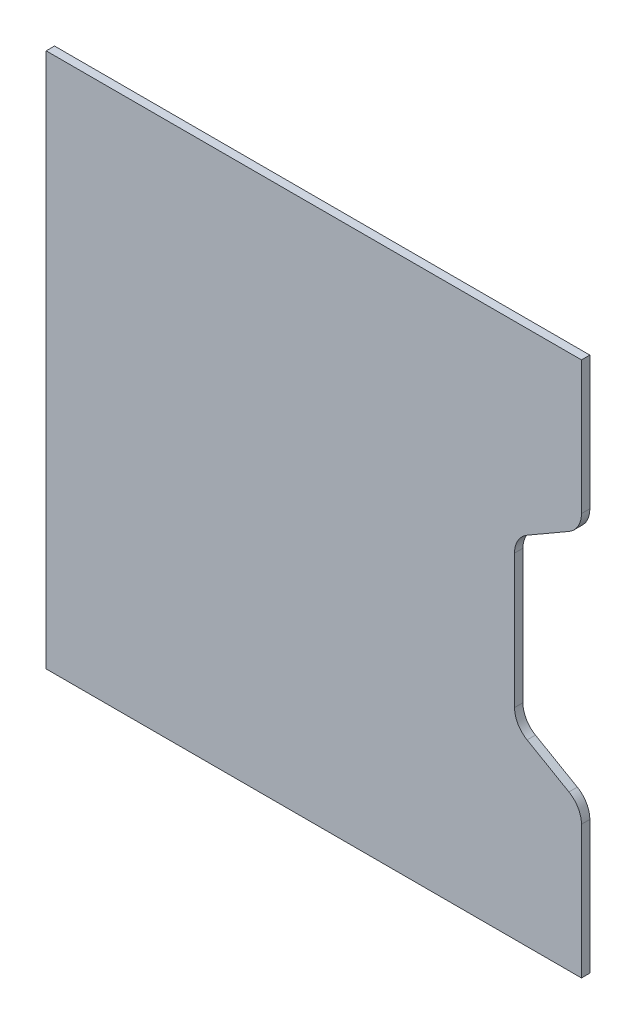
SolidWorks part; units mm, degrees
ref_plane "Front Plane" through (0, 0, 0) normal (0, 0, 1) x (1, 0, 0)
ref_plane "Top Plane" through (0, 0, 0) normal (0, 1, 0) x (1, 0, 0)
ref_plane "Right Plane" through (0, 0, 0) normal (1, 0, 0) x (0, 0, -1)
sketch "Sketch1" plane through (0, 0, 0) normal (0, 0, 1) x (1, 0, 0)
  line L1 (-101.6, -101.6) -> (101.6, -101.6)
  line L2 (-101.6, -101.6) -> (-101.6, 101.6)
  line L3 (-101.6, 101.6) -> (101.6, 101.6)
  line L4 (101.6, -101.6) -> (101.6, 101.6)
  line L5 (-101.6, -101.6) -> (101.6, 101.6) construction
  line L6 (-101.6, 101.6) -> (101.6, -101.6) construction
  point P0 (0, 0)
  dimension "D1" = 203.2
  dimension "D2" = 203.2
extrude "Boss-Extrude1" add sketch "Sketch1" against normal blind 3.175
sketch "Sketch4" plane through (0, 0, 0) normal (1, 0, 0) x (0, 0, -1)
  line L0 (0, 101.6) -> (0, -101.6) construction
  line L1 (0, 63.5) -> (-1.9844, 63.5)
  line L2 (0, 63.5) -> (0, 101.6)
  line L3 (0, 101.6) -> (-0.4801, 103.5254) construction
  line L4 (-1.9844, 63.5) -> (-1.9844, 101.6)
  line L5 (36.9683, 110.8172) -> (0, 101.6)
  line L6 (36.9683, 110.8172) -> (36.4882, 112.7427)
  line L7 (0, 101.6) -> (-1.9844, 101.6) construction
  line L8 (36.4882, 112.7427) -> (-0.4801, 103.5254)
  arc A0 (-0.4801, 103.5254) -> (-1.9844, 101.6) centre (-5.5035, 105.8998) ccw
  circle A1 centre (-5.5035, 105.8998) radius 3.7507
  dimension "D4" = 5.5562
  dimension "D1" = 1.9844
  dimension "D2" = 104
  dimension "D3" = 38.1
  dimension "D6" = 38.1
extrude "Boss-Extrude2" [suppressed] add sketch "Sketch4" along normal mid plane 203.2 separate body
sketch "Sketch5" [suppressed] plane through (0, 0, 1.9844) normal (0, 0, 1) x (1, 0, 0)
  line L0 (101.6, 63.5) -> (-101.6, 63.5) construction
  line L1 (-12.7, 63.5) -> (12.7, 63.5)
  line L2 (-12.7, 63.5) -> (-12.7, 116.2378)
  line L3 (-12.7, 116.2378) -> (12.7, 116.2378)
  line L4 (12.7, 63.5) -> (12.7, 116.2378)
  line L5 (-101.6, 101.6) -> (-101.6, 63.5) construction
  line L6 (101.6, 101.6) -> (101.6, 63.5) construction
  line L7 (-93.6625, 80.9625) -> (-101.6, 80.9625) construction
  line L8 (-93.6625, 80.9625) -> (-20.6375, 80.9625) construction
  line L9 (101.6, 101.6) -> (-101.6, 101.6) construction
  line L11 (0, 101.6) -> (0, 63.5) construction
  line L12 (-20.6375, 80.9625) -> (-12.7, 80.9625) construction
  line L13 (-57.15, 80.9625) -> (-57.15, 72.2313) construction
  line L14 (-57.15, 72.2313) -> (-57.15, 63.5) construction
  circle A0 centre (-93.6625, 80.9625) radius 4.3656
  circle A1 centre (-20.6375, 80.9625) radius 4.3656
  circle A2 centre (20.6375, 80.9625) radius 4.3656
  circle A3 centre (93.6625, 80.9625) radius 4.3656
  circle A4 centre (-57.15, 72.2313) radius 4.3656
  circle A5 centre (57.15, 72.2312) radius 4.3656
  dimension "D5" = 8.7312
  dimension "D3" = 8.7312
  dimension "D1" = 88.9
  dimension "D2" = 88.9
  dimension "D4" = 17.4625
  dimension "D6" = 7.9375
extrude "Cut-Extrude1" [suppressed] cut sketch "Sketch5" against normal through all both and the other way through all
sketch "Sketch6" [suppressed] plane through (0, 97.5792, 24.3292) normal (0, 0.9703, 0.2419) x (1, 0, 0)
  line L0 (101.6, 62.6793) -> (12.7, 62.6793) construction
  line L1 (12.7, 62.6793) -> (12.7, 24.5793) construction
  line L2 (-12.7, 24.5793) -> (-12.7, 62.6793) construction
  line B0 (93.6625, 45.2168) -> (101.6, 45.2168) construction
  line B1 (93.6625, 45.2168) -> (20.6375, 45.2168) construction
  line B2 (20.6375, 45.2168) -> (12.7, 45.2168) construction
  line B3 (57.15, 45.2168) -> (57.15, 53.948) construction
  line B4 (57.15, 53.948) -> (57.15, 62.6793) construction
  circle B5 centre (93.6625, 45.2168) radius 4.3656
  circle B6 centre (20.6375, 45.2168) radius 4.3656
  circle B7 centre (57.15, 53.948) radius 4.3656
  circle B8 centre (-20.6375, 43.6293) radius 4.3656
  circle B9 centre (-93.6625, 43.6293) radius 4.3656
  circle B10 centre (-57.15, 52.3605) radius 4.3656
sketch_block_instance "Block2-1"
sketch_block "Block2" parameters "D1"=8.7312
sketch_block_instance "Block2-2"
extrude "Cut-Extrude2" [suppressed] cut sketch "Sketch6" against normal through all
sketch "Sketch8" plane through (0, 0, 0) normal (0, 0, 1) x (1, 0, 0)
  line L0 (0, 0) -> (0, 57) construction
  line L1 (-49.3634, -28.5) -> (0, 0) construction
  line L2 (49.3634, -28.5) -> (0, 0) construction
  circle A0 centre (0, 0) radius 50.5
  circle A1 centre (0, 0) radius 57 construction
  circle A2 centre (0, 57) radius 4.25
  circle A3 centre (-49.3634, -28.5) radius 4.25
  circle A4 centre (49.3634, -28.5) radius 4.25
  dimension "D1" = 101
  dimension "D4" = 114
  dimension "D5" = 8.5
  dimension "D2" = 120
  dimension "D3" = 120
extrude "Cut-Extrude3" [suppressed] cut sketch "Sketch8" against normal through all
sketch "Sketch9" plane through (0, 0, 0) normal (0, 0, 1) x (1, 0, 0)
  line L0 (-101.6, 101.6) -> (-101.6, -101.6) construction
  line L1 (-101.6, -101.6) -> (101.6, -101.6) construction
  line L2 (50.8, -68.9615) -> (-101.6, -68.9615) construction
  line L3 (76.2, -82.4981) -> (-76.2, -82.4981) construction
  line L4 (-25.4, -82.4981) -> (-25.4, -75.7298) construction
  line L5 (-25.4, -75.7298) -> (-25.4, -68.9615) construction
  line L6 (25.4, -75.7298) -> (-76.2, -75.7298) construction
  circle A0 centre (25.4, -75.7298) radius 2.5273
  circle A1 centre (-25.4, -75.7298) radius 2.5273
  circle A2 centre (-76.2, -75.7298) radius 2.5273
  dimension "D1" = 5.0546
  dimension "D2" = 101.6
  dimension "D3" = 13.5366
  dimension "D4" = 152.4
  dimension "D5" = 19.1019
extrude "Boss-Extrude5" [suppressed] add sketch "Sketch9" against normal blind 41.275
sketch "Sketch10" plane through (0, 0, 0) normal (0, 0, 1) x (1, 0, 0)
  line L0 (101.6, -101.6) -> (101.6, -51.0632) construction
  line L1 (101.6, -101.6) -> (101.6, 101.6) construction
  line L2 (96.8375, 42.8143) -> (80.9625, 33.6489)
  line L3 (76.2, 25.4) -> (76.2, -25.4)
  line L4 (80.9625, -33.6489) -> (96.8375, -42.8143)
  line L6 (101.6, -51.0632) -> (101.6, 51.0632)
  arc A0 (76.2, -25.4) -> (80.9625, -33.6489) centre (85.725, -25.4) ccw
  arc A1 (80.9625, 33.6489) -> (76.2, 25.4) centre (85.725, 25.4) ccw
  arc A2 (101.6, 51.0632) -> (96.8375, 42.8143) centre (92.075, 51.0632) cw
  arc A3 (96.8375, -42.8143) -> (101.6, -51.0632) centre (92.075, -51.0632) cw
  dimension "D1" = 9.525
  dimension "D2" = 50.8
  dimension "D5" = 120
extrude "Cut-Extrude4" cut sketch "Sketch10" against normal through all
